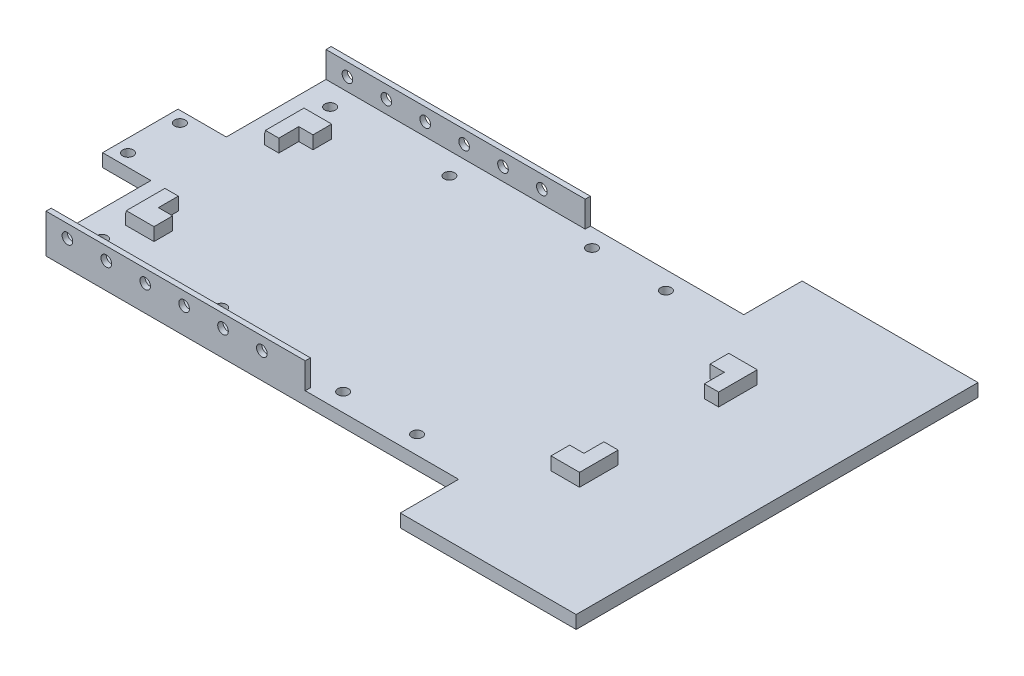
SolidWorks part; units mm, degrees
material "PLA"
ref_plane "Front Plane" through (0, 0, 0) normal (0, 0, 1) x (1, 0, 0)
ref_plane "Top Plane" through (0, 0, 0) normal (0, 1, 0) x (1, 0, 0)
ref_plane "Right Plane" through (0, 0, 0) normal (1, 0, 0) x (0, 0, -1)
sketch "Sketch1" plane through (0, 0, 0) normal (0, 1, 0) x (1, 0, 0)
  line L1 (-33.5, 77.5) -> (33.5, 77.5)
  line L2 (-33.5, 77.5) -> (-33.5, -77.5)
  line L3 (-33.5, -77.5) -> (33.5, -77.5)
  line L4 (33.5, 77.5) -> (33.5, -77.5)
  line L5 (-33.5, 77.5) -> (33.5, -77.5) construction
  line L6 (-33.5, -77.5) -> (33.5, 77.5) construction
  line L7 (-193.5, 55) -> (-33.5, 55)
  line L8 (-193.5, 55) -> (-193.5, -55)
  line L9 (-193.5, -55) -> (-33.5, -55)
  line L10 (-33.5, 55) -> (-33.5, -55)
  line L11 (-212.12, 14.55) -> (-193.5, 14.55)
  line L12 (-212.12, 14.55) -> (-212.12, -14.55)
  line L13 (-212.12, -14.55) -> (-193.5, -14.55)
  line L14 (-193.5, 14.55) -> (-193.5, -14.55)
  point P0 (0, 0)
  point P10 (-193.5, 0)
  point P15 (-212.12, 0)
  dimension "D1" = 67
  dimension "D2" = 155
  dimension "D3" = 160
  dimension "D4" = 110
  dimension "D5" = 29.1
  dimension "D6" = 18.62
extrude "Boss-Extrude1" add sketch "Sketch1" along normal blind 5
sketch "Sketch4" plane through (0, 5, 0) normal (0, 1, 0) x (1, 0, 0)
  line L0 (-55, 0) -> (55, 0) construction
  line L1 (-193.5, -55) -> (-93.5, -55)
  line L2 (-193.5, -55) -> (-193.5, -53)
  line L3 (-193.5, -53) -> (-93.5, -53)
  line L4 (-93.5, -55) -> (-93.5, -53)
  line L10 (-193.5, -55) -> (-33.5, -55) construction
  line L11 (-193.5, -14.55) -> (-193.5, -55) construction
  line L12 (-193.5, 53) -> (-93.5, 53)
  line L13 (-93.5, 55) -> (-93.5, 53)
  line L14 (-193.5, 55) -> (-93.5, 55)
  line L15 (-193.5, 55) -> (-193.5, 53)
  point P14 (-193.5, -54)
  dimension "D1" = 100
  dimension "D2" = 2
extrude "Boss-Extrude2" add sketch "Sketch4" along normal blind 10
sketch "Sketch9" plane through (0, 5, 0) normal (0, 1, 0) x (1, 0, 0)
  line L0 (-33.5, -77.5) -> (33.5, -77.5) construction
  line L1 (-33.5, -55) -> (-34.3458, -55)
  line L2 (-33.5, -55) -> (-33.5, -77.5)
  line L3 (-33.5, -77.5) -> (-34.3458, -77.5)
  line L4 (-34.3458, -55) -> (-34.3458, -77.5)
  line L5 (-55, 0) -> (55, 0) construction
  line L6 (-33.5, 77.5) -> (-34.3458, 77.5)
  line L7 (-34.3458, 55) -> (-34.3458, 77.5)
  line L8 (-33.5, 55) -> (-34.3458, 55)
  line L9 (-33.5, 55) -> (-33.5, 77.5)
extrude "Boss-Extrude4" add sketch "Sketch9" against normal blind 5
sketch "Sketch5" plane through (0, 5, 0) normal (0, 1, 0) x (1, 0, 0)
  line L1 (-178, 27) -> (-172.5, 27)
  line L2 (-178, 27) -> (-178, 19.3)
  line L3 (-178, -27.15) -> (-172.5, -27.15)
  line L4 (-13.85, 27) -> (-13.85, 19.3)
  line L5 (-172.5, 27) -> (-172.5, 34.2)
  line L6 (-172.5, 34.2) -> (-183.5, 34.2)
  line L7 (-183.5, 34.2) -> (-183.5, 19.3)
  line L8 (-183.5, 19.3) -> (-178, 19.3)
  line L9 (-19.35, -27.15) -> (-19.35, -34.35)
  line L10 (-19.35, 27) -> (-19.35, 34.2)
  line L11 (-19.35, 34.2) -> (-8.35, 34.2)
  line L12 (-8.35, 34.2) -> (-8.35, 19.3)
  line L13 (-8.35, 19.3) -> (-13.85, 19.3)
  line L14 (-19.35, -34.35) -> (-8.35, -34.35)
  line L15 (-8.35, -34.35) -> (-8.35, -19.45)
  line L16 (-8.35, -19.45) -> (-13.85, -19.45)
  line L17 (-172.5, -27.15) -> (-172.5, -34.35)
  line L18 (-172.5, -34.35) -> (-183.5, -34.35)
  line L19 (-183.5, -34.35) -> (-183.5, -19.45)
  line L20 (-183.5, -19.45) -> (-178, -19.45)
  line L21 (-178, -19.45) -> (-178, -27.15)
  line L22 (-19.35, -27.15) -> (-13.85, -27.15)
  line L23 (-19.35, 27) -> (-13.85, 27)
  line L24 (-13.85, -19.45) -> (-13.85, -27.15)
  line L25 (-193.5, 53) -> (-193.5, 14.55) construction
  point P12 (-178, 34.2)
  point P20 (-13.85, 34.2)
  point P24 (-13.85, -34.35)
  point P33 (-178, -34.35)
  dimension "D1" = 164.15
  dimension "D2" = 54.15
  dimension "D3" = 11
  dimension "D4" = 7.2
  dimension "D5" = 14.9
  dimension "D6" = 5.5
  dimension "D7" = 7.2
  dimension "D8" = 11
  dimension "D9" = 14.9
  dimension "D10" = 5.5
  dimension "D11" = 11
  dimension "D12" = 14.9
  dimension "D13" = 7.2
  dimension "D14" = 5.5
  dimension "D15" = 7.2
  dimension "D16" = 11
  dimension "D17" = 14.9
  dimension "D18" = 5.5
  dimension "D19" = 10
extrude "Boss-Extrude3" add sketch "Sketch5" along normal blind 5
sketch "Sketch7" plane through (0, 5, 0) normal (0, 1, 0) x (1, 0, 0)
  line L2 (-212.12, 14.55) -> (-212.12, -14.55) construction
  circle A0 centre (-207.12, 10.268) radius 2.05
  circle A1 centre (-207.12, -9.742) radius 2.05
  dimension "D1" = 4.1
  dimension "D2" = 4.1
  dimension "D4" = 5
  dimension "D3" = 20.01
extrude "Cut-Extrude2" cut sketch "Sketch7" against normal blind 10
sketch "Sketch14" plane through (0, 0, 77.5) normal (0, 0, 1) x (1, 0, 0)
  line L0 (-34.3458, 0) -> (33.5, 0) construction
  line L1 (28.85, -4.13) -> (-11.15, -4.13)
  line L2 (28.85, -4.13) -> (28.85, 0)
  line L3 (28.85, 0) -> (-11.15, 0)
  line L4 (-11.15, -4.13) -> (-11.15, 0)
  line L5 (33.5, 5) -> (33.5, 0) construction
  dimension "D1" = 4.13
  dimension "D2" = 40
  dimension "D3" = 4.65
extrude "Boss-Extrude5" [suppressed] add sketch "Sketch14" against normal blind 32
sketch "Sketch15" plane through (0, 0, -77.5) normal (0, 0, -1) x (-1, 0, 0)
  line L0 (-33.5, 5) -> (-33.5, 0) construction
  line L1 (-28.85, 0) -> (11.15, 0)
  line L2 (-28.85, 0) -> (-28.85, -4.13)
  line L3 (-28.85, -4.13) -> (11.15, -4.13)
  line L4 (11.15, 0) -> (11.15, -4.13)
  line L7 (34.3458, 0) -> (-33.5, 0) construction
  dimension "D1" = 40
  dimension "D2" = 4.13
  dimension "D3" = 4.65
extrude "Boss-Extrude6" [suppressed] add sketch "Sketch15" against normal blind 32
sketch "Sketch6" plane through (0, 5, 0) normal (0, 1, 0) x (1, 0, 0)
  line L0 (-93.5, -53) -> (-193.5, -53) construction
  line L5 (-55, 0) -> (55, 0) construction
  circle A0 centre (-85.881, -48) radius 2.05
  circle A1 centre (-57.381, -48) radius 2.05
  circle A2 centre (-57.381, 48) radius 2.05
  circle A3 centre (-85.881, 48) radius 2.05
  dimension "D1" = 4.1
  dimension "D2" = 5
  dimension "D4" = 4.1
  dimension "D6" = 4.1
  dimension "D7" = 4.1
  dimension "D5" = 28.5
extrude "Cut-Extrude1" cut sketch "Sketch6" against normal through all
sketch "Sketch10" plane through (0, 5, 0) normal (0, 1, 0) x (1, 0, 0)
  line L2 (-193.5, 53) -> (-193.5, 14.55) construction
  line L3 (-193.5, -14.55) -> (-193.5, -53) construction
  circle A0 centre (-183.5, 44.5998) radius 2.05
  circle A1 centre (-137.5, 44.5998) radius 2.05
  circle A2 centre (-183.5, -43.4002) radius 2.05
  circle A3 centre (-137.5, -43.4002) radius 2.05
  dimension "D1" = 4.1
  dimension "D2" = 4.1
  dimension "D4" = 4.1
  dimension "D5" = 4.1
  dimension "D3" = 46
  dimension "D8" = 10
  dimension "D9" = 10
  dimension "D6" = 88
extrude "Cut-Extrude4" cut sketch "Sketch10" against normal blind 10
fillet "Fillet1" radius 0.3 2 edges at (-34.3458, 2.5, -55) (-34.3458, 2.5, 55)
sketch "Sketch16" plane through (0, 0, 55) normal (0, 0, 1) x (1, 0, 0)
  line L0 (-193.5, 15) -> (-93.5, 15) construction
  line L1 (-140.2282, 10) -> (-125.2282, 10) construction
  line L2 (-140.2282, 10) -> (-155.2282, 10) construction
  circle A0 centre (-140.2282, 10) radius 2.05
  circle A1 centre (-125.2282, 10) radius 2.05
  circle A2 centre (-110.2282, 10) radius 2.05
  circle A3 centre (-155.2282, 10) radius 2.05
  circle A4 centre (-170.2282, 10) radius 2.05
  circle A5 centre (-185.2282, 10) radius 2.05
  dimension "D1" = 5
  dimension "D2" = 4.1
  dimension "D4" = 15
  dimension "D6" = 15
  dimension "D3" = 3
  dimension "D5" = 4
extrude "Cut-Extrude5" cut sketch "Sketch16" against normal through all
equation "\"D2@Sketch10\"=\"D1@Sketch10\""
equation "\"D4@Sketch10\"=\"D1@Sketch10\""
equation "\"D5@Sketch10\"=\"D1@Sketch10\""
